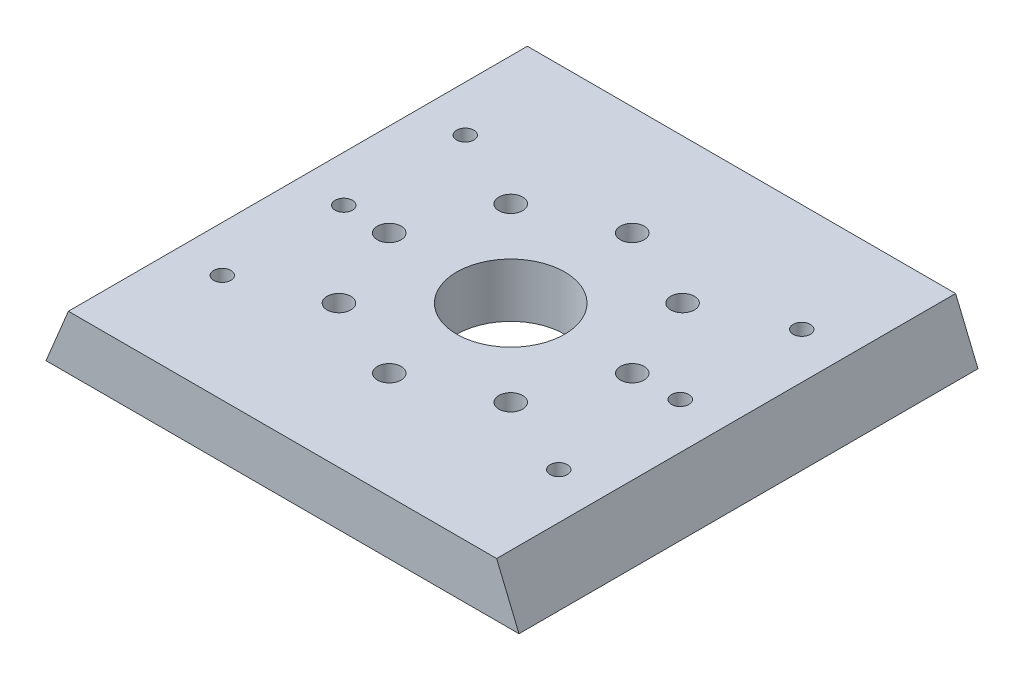
SolidWorks part; units mm, degrees
ref_plane "Front Plane" through (0, 0, 0) normal (0, 0, 1) x (1, 0, 0)
ref_plane "Top Plane" through (0, 0, 0) normal (0, 1, 0) x (1, 0, 0)
ref_plane "Right Plane" through (0, 0, 0) normal (1, 0, 0) x (0, 0, -1)
sketch "Sketch2" plane through (0, 0, 0) normal (0, 0, 1) x (1, 0, 0)
  line L0 (0, 0) -> (87.5943, 0)
  line L1 (87.5943, 0) -> (83.4521, 10)
  line L2 (83.4521, 10) -> (4.1421, 10)
  line L3 (4.1421, 10) -> (0, 0)
  dimension "D1" = 79.31
  dimension "D2" = 112.5
  dimension "D3" = 112.5
  dimension "D4" = 10
extrude "Boss-Extrude1" add sketch "Sketch2" along normal blind 85
sketch "Sketch3" plane through (0, 10, 0) normal (0, 1, 0) x (1, 0, 0)
  line L0 (43.7971, 0) -> (43.7971, -85) construction
  line L1 (83.4521, 0) -> (4.1421, 0) construction
  line L2 (83.4521, -85) -> (4.1421, -85) construction
  line L3 (4.1421, -42.5) -> (83.4521, -42.5) construction
  line L4 (4.1421, -85) -> (4.1421, 0) construction
  line L5 (83.4521, -85) -> (83.4521, 0) construction
  circle A0 centre (43.7971, -42.735) radius 10
  circle A1 centre (43.7971, -20.235) radius 2.2
  circle A2 centre (59.707, -26.8251) radius 2.2
  circle A3 centre (66.2971, -42.735) radius 2.2
  circle A4 centre (59.707, -58.6449) radius 2.2
  circle A5 centre (43.7971, -65.235) radius 2.2
  circle A6 centre (27.8872, -58.6449) radius 2.2
  circle A7 centre (21.2971, -42.735) radius 2.2
  circle A8 centre (27.8872, -26.8251) radius 2.2
  point P30 (43.7971, -42.735)
  dimension "D1" = 22.5
extrude "Cut-Extrude1" cut sketch "Sketch3" against normal blind 85
sketch "Sketch4" plane through (0, 10, 0) normal (0, 1, 0) x (1, 0, 0)
  line L0 (43.7971, 0) -> (43.7971, -85) construction
  line L1 (83.4521, 0) -> (4.1421, 0) construction
  line L2 (83.4521, -85) -> (4.1421, -85) construction
  line L3 (4.1421, -42.5) -> (83.4521, -42.5) construction
  line L4 (4.1421, -85) -> (4.1421, 0) construction
  line L5 (83.4521, -85) -> (83.4521, 0) construction
  circle A0 centre (12.6421, -20) radius 1.6
  circle A2 centre (12.6421, -42.5) radius 1.6
  circle A3 centre (12.6421, -65) radius 1.6
  circle A4 centre (74.9521, -65) radius 1.6
  circle A5 centre (74.9521, -42.5) radius 1.6
  circle A6 centre (74.9521, -20) radius 1.6
  dimension "D1" = 3.2
  dimension "D4" = 3.2
  dimension "D5" = 8.5
  dimension "D2" = 8.5
  dimension "D3" = 20
extrude "Cut-Extrude2" cut sketch "Sketch4" against normal blind 85
